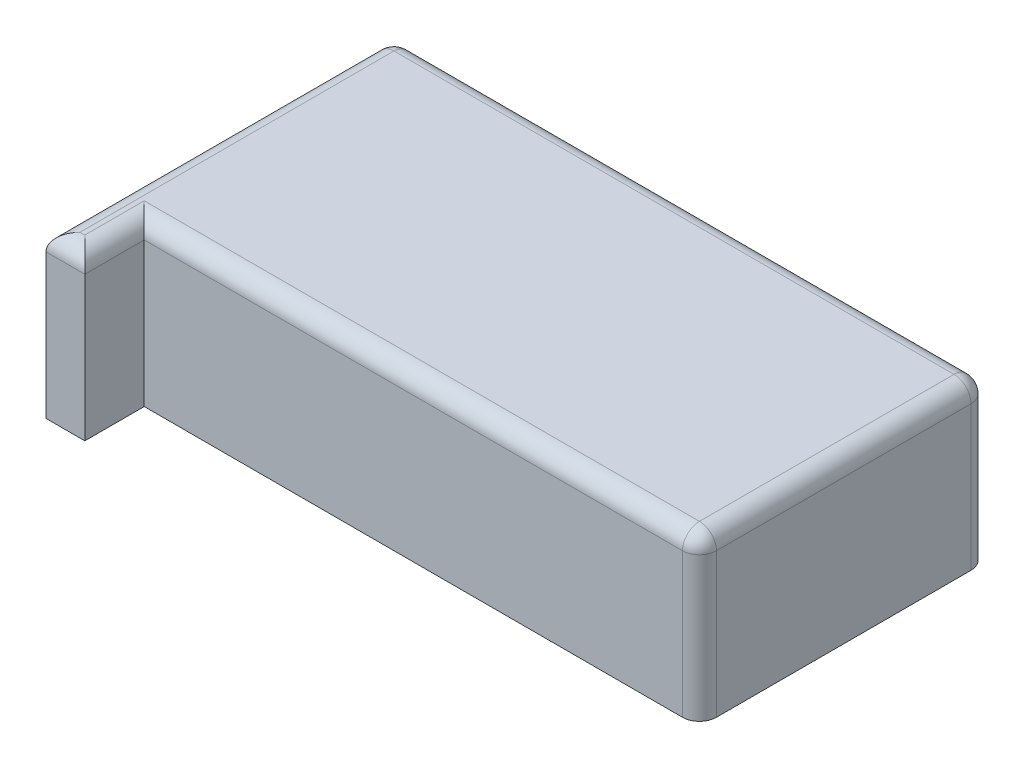
SolidWorks part; units mm, degrees
ref_plane "Front Plane" through (0, 0, 0) normal (0, 0, 1) x (1, 0, 0)
ref_plane "Top Plane" through (0, 0, 0) normal (0, 1, 0) x (1, 0, 0)
ref_plane "Right Plane" through (0, 0, 0) normal (1, 0, 0) x (0, 0, -1)
sketch "Sketch1" plane through (0, 0, 0) normal (0, 1, 0) x (1, 0, 0)
  line L1 (0, 0) -> (70, 0)
  line L2 (0, 0) -> (0, 34)
  line L3 (0, 34) -> (70, 34)
  line L4 (70, 0) -> (70, 34)
  dimension "D1" = 34
  dimension "D2" = 70
extrude "Boss-Extrude1" add sketch "Sketch1" along normal blind 19
sketch "Sketch2" plane through (0, 0, 0) normal (0, 0, 1) x (1, 0, 0)
  line L0 (0, 0) -> (70, 0) construction
  line L1 (0, 19) -> (4.5744, 19)
  line L2 (0, 19) -> (0, 0)
  line L3 (0, 0) -> (4.5744, 0)
  line L4 (4.5744, 19) -> (4.5744, 0)
extrude "Boss-Extrude2" add sketch "Sketch2" along normal blind 7
fillet "Fillet2" radius 2 2 edges at (35, 19, -34) (37.2872, 19, 0)
fillet "Fillet3" radius 2 10 edges at (0, 8.5, -34) (0, 18.4142, -33.4142) (70, 8.5, 0) (70, 18.4142, -0.5858) (70, 18.4142, -33.4142) (4.5744, 19, 2.5) (2.2872, 19, 7) (0, 19, -12.5) (70, 19, -17) (70, 8.5, -34)
